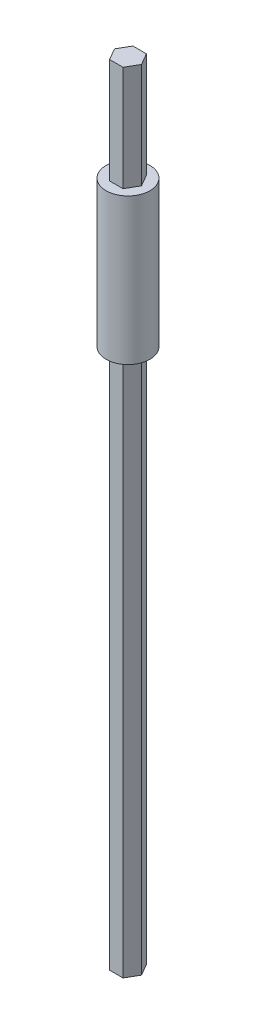
SolidWorks part; units mm, degrees
ref_plane "Alzado" through (0, 0, 0) normal (0, 0, 1) x (1, 0, 0)
ref_plane "Planta" through (0, 0, 0) normal (0, 1, 0) x (1, 0, 0)
ref_plane "Vista lateral" through (0, 0, 0) normal (1, 0, 0) x (0, 0, -1)
sketch "Croquis2" plane through (0, 71.3, 0) normal (0, 1, 0) x (1, 0, 0)
  circle A2 centre (1.5556, 1.5556) radius 3.75
extrude "Saliente-Extruir2" add sketch "Croquis2" along normal blind 25
sketch "Croquis3" plane through (0, 96.3, 0) normal (0, 1, 0) x (1, 0, 0)
  line L7 (3.865, 1.5556) -> (2.7103, 3.5556)
  line L8 (2.7103, 3.5556) -> (0.4009, 3.5556)
  line L9 (0.4009, 3.5556) -> (-0.7538, 1.5556)
  line L10 (-0.7538, 1.5556) -> (0.4009, -0.4444)
  line L11 (0.4009, -0.4444) -> (2.7103, -0.4444)
  line L12 (2.7103, -0.4444) -> (3.865, 1.5556)
  circle A2 centre (1.5556, 1.5556) radius 2 construction
extrude "Saliente-Extruir4" add sketch "Croquis3" along normal blind 18
sketch "Croquis4" plane through (0, 71.3, 0) normal (0, -1, 0) x (1, 0, 0)
  line L1 (3.865, -1.5556) -> (2.7103, 0.4444)
  line L2 (2.7103, 0.4444) -> (0.4009, 0.4444)
  line L3 (0.4009, 0.4444) -> (-0.7538, -1.5556)
  line L4 (-0.7538, -1.5556) -> (0.4009, -3.5556)
  line L5 (0.4009, -3.5556) -> (2.7103, -3.5556)
  line L6 (2.7103, -3.5556) -> (3.865, -1.5556)
  circle A0 centre (1.5556, -1.5556) radius 2 construction
extrude "Saliente-Extruir6" add sketch "Croquis4" along normal blind 92
